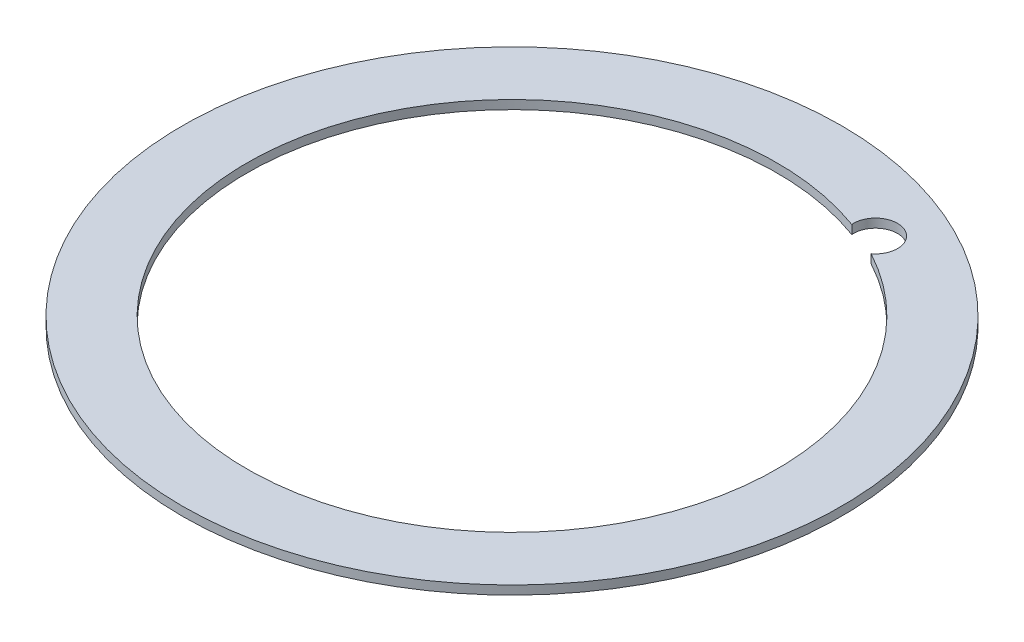
SolidWorks part; units mm, degrees
ref_plane "Front Plane" through (0, 0, 0) normal (0, 0, 1) x (1, 0, 0)
ref_plane "Top Plane" through (0, 0, 0) normal (0, 1, 0) x (1, 0, 0)
ref_plane "Right Plane" through (0, 0, 0) normal (1, 0, 0) x (0, 0, -1)
sketch "Sketch1" plane through (0, 0, 0) normal (0, 1, 0) x (1, 0, 0)
  circle A0 centre (0, 0) radius 142.875
  circle A4 centre (0, 0) radius 114.935
  circle A6 centre (0, 0) radius 114.935 construction
  circle A7 centre (48.7795, 108.8202) radius 9.525 construction
  circle A8 centre (48.7795, 108.8202) radius 9.525
  point P6 (0, 0)
  dimension "D1" = 285.75
extrude "Boss-Extrude2" add sketch "Sketch1" against normal blind 3.81
